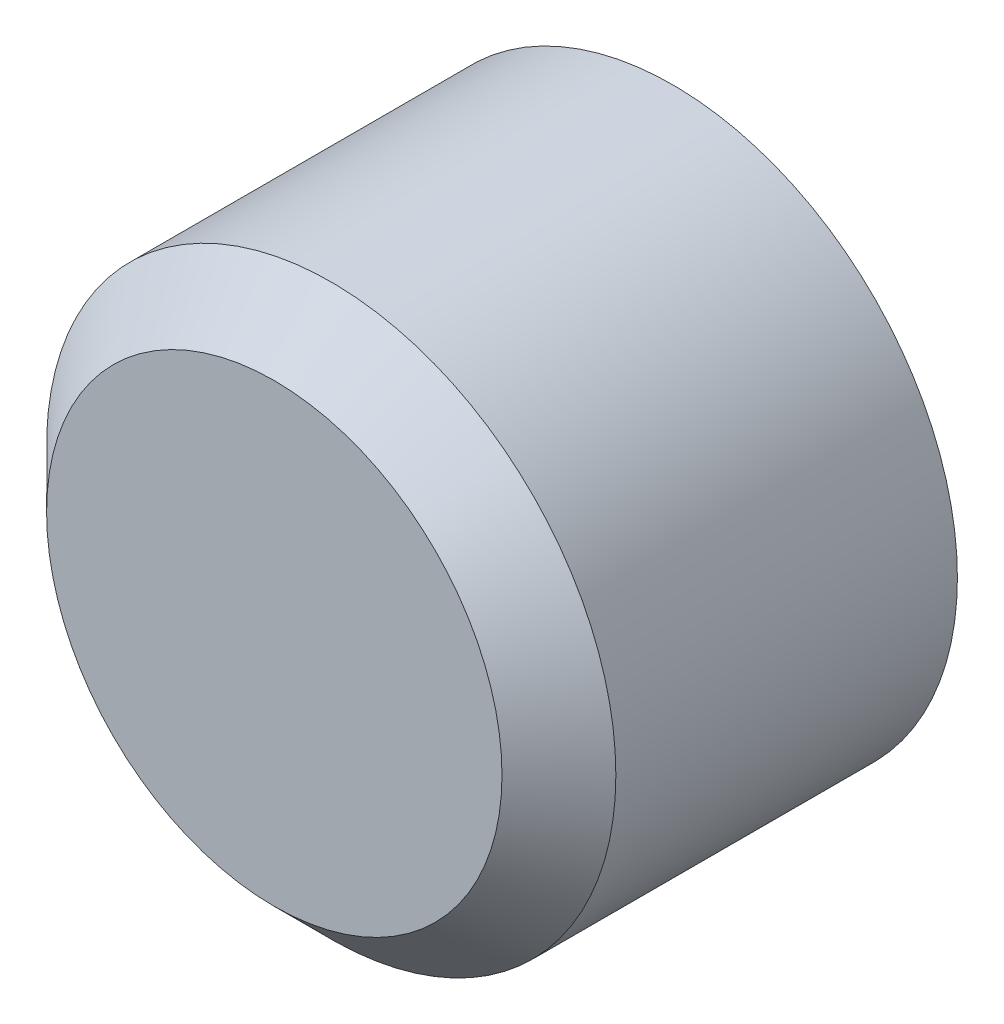
SolidWorks part; units mm, degrees
material "6061 Alloy"
ref_plane "Front Plane" through (0, 0, 0) normal (0, 0, 1) x (1, 0, 0)
ref_plane "Top Plane" through (0, 0, 0) normal (0, 1, 0) x (1, 0, 0)
ref_plane "Right Plane" through (0, 0, 0) normal (1, 0, 0) x (0, 0, -1)
sketch "Sketch1" plane through (0, 0, 0) normal (0, 0, 1) x (1, 0, 0)
  circle A0 centre (0, 0) radius 5
  dimension "D1" = 10
extrude "Boss-Extrude1" add sketch "Sketch1" along normal blind 7
chamfer "Chamfer1" distance 1 angle 45 1 edges at (5, 0, 7)
